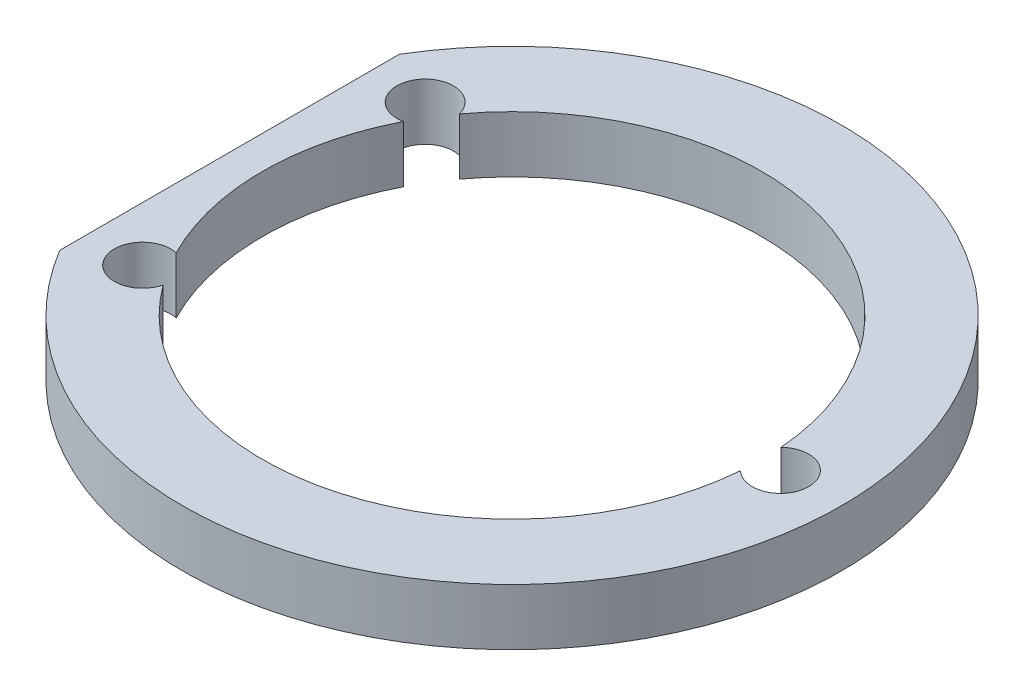
SolidWorks part; units mm, degrees
ref_plane "前视基准面" through (0, 0, 0) normal (0, 0, 1) x (1, 0, 0)
ref_plane "上视基准面" through (0, 0, 0) normal (0, 1, 0) x (1, 0, 0)
ref_plane "右视基准面" through (0, 0, 0) normal (1, 0, 0) x (0, 0, -1)
sketch "草图1" plane through (0, 0, 0) normal (0, 1, 0) x (1, 0, 0)
  line L0 (0, 0) -> (41.8537, 0) construction
  line L1 (0, 0) -> (0, 19.6189) construction
  line L2 (-30, 18.0278) -> (-30, -18.0278)
  circle A0 centre (0, 0) radius 28.5 construction
  arc A1 (-21.3242, 15.7331) -> (-23.592, 12.0693) centre (-24.2332, 15) ccw
  arc A2 (-21.3242, -15.7331) -> (-23.592, -12.0693) centre (-24.2332, -15) cw
  arc A3 (26.4123, -2.1544) -> (26.4123, 2.1544) centre (28.5, 0) ccw
  arc A4 (-30, -18.0278) -> (-30, 18.0278) centre (0, 0) ccw
  arc A5 (-23.592, 12.0693) -> (-23.592, -12.0693) centre (0, 0) ccw
  arc A6 (26.4123, 2.1544) -> (-21.3242, 15.7331) centre (0, 0) ccw
  arc A7 (-21.3242, -15.7331) -> (26.4123, -2.1544) centre (0, 0) ccw
  dimension "D1" = 57
  dimension "D2" = 30
  dimension "D3" = 6
  dimension "D4" = 6
  dimension "D6" = 53
  dimension "D7" = 70
  dimension "D8" = 30
extrude "凸台-拉伸1" add sketch "草图1" along normal blind 6
